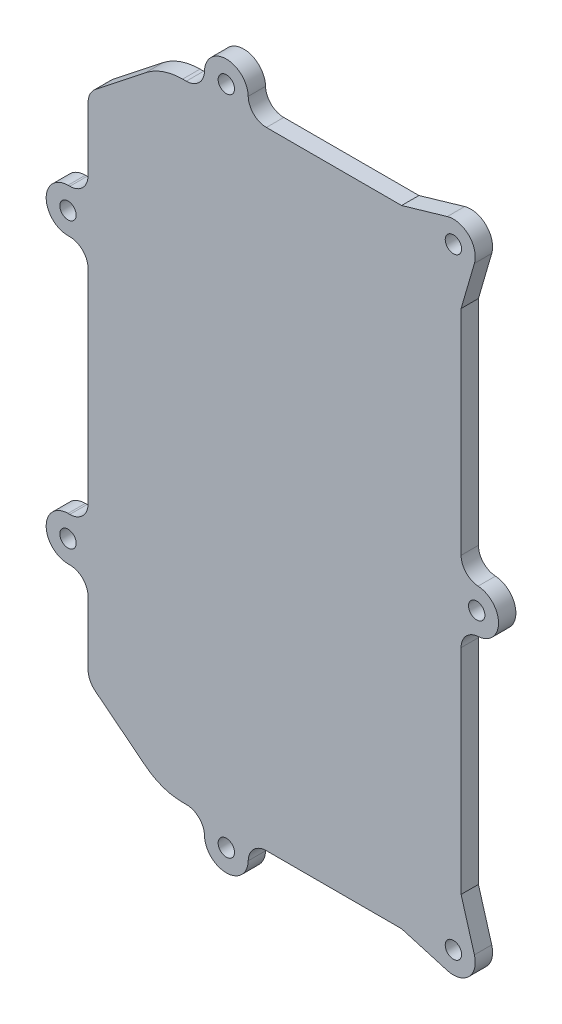
SolidWorks part; units mm, degrees
material "Acrylic (Medium-high impact)"
ref_plane "X-Y Datum" through (0, 0, 0) normal (0, 0, 1) x (1, 0, 0)
ref_plane "X-Z Datum" through (0, 0, 0) normal (0, 1, 0) x (1, 0, 0)
ref_plane "Y-Z Datum" through (0, 0, 0) normal (1, 0, 0) x (0, 0, -1)
sketch "Sketch1" plane through (0, 0, 0) normal (0, 0, 1) x (1, 0, 0)
  line L19 (-94.0226, 36.54) -> (-94.0226, 19.1784)
  line L20 (-99.5226, 41.54) -> (-99.0226, 41.54)
  line L21 (-99.0226, 53.54) -> (-99.5226, 53.54)
  line L22 (-94.0226, 114.5767) -> (-94.0226, 58.54)
  line L23 (-99.5226, 119.5767) -> (-99.0226, 119.5767)
  line L24 (-99.0226, 131.5767) -> (-99.5226, 131.5767)
  line L25 (-94.0226, 153.9383) -> (-94.0226, 136.5767)
  line L26 (-78.1621, 169.0446) -> (-91.9938, 158.1249)
  line L27 (-67.0387, 172.5583) -> (-68.0408, 172.5583)
  line L28 (-7.9166, 172.5583) -> (-45.043, 172.5583)
  line L31 (4.6315, 176.21) -> (-7.9166, 172.5583)
  line L33 (8.4174, 156.2243) -> (12.0691, 168.7725)
  line L35 (8.4174, 97.5349) -> (8.4174, 156.2243)
  line L36 (8.4174, 16.8923) -> (8.4174, 75.5817)
  line L38 (12.0691, 4.3442) -> (8.4174, 16.8923)
  line L39 (-7.9166, 0.5583) -> (4.6315, -3.0933)
  line L40 (-45.043, 0.5583) -> (-7.9166, 0.5583)
  line L42 (-68.0408, 0.5583) -> (-67.0387, 0.5583)
  line L43 (-91.9938, 14.9918) -> (-78.1621, 4.0721)
  line L94 (-94.0226, 36.54) -> (-94.0226, 19.1784)
  line L95 (-99.5226, 41.54) -> (-99.0226, 41.54)
  line L96 (-99.0226, 53.54) -> (-99.5226, 53.54)
  line L97 (-94.0226, 114.5767) -> (-94.0226, 58.54)
  line L98 (-99.5226, 119.5767) -> (-99.0226, 119.5767)
  line L99 (-99.0226, 131.5767) -> (-99.5226, 131.5767)
  line L100 (-94.0226, 153.9383) -> (-94.0226, 136.5767)
  line L101 (-78.1621, 169.0446) -> (-91.9938, 158.1249)
  line L102 (-67.0387, 172.5583) -> (-68.0408, 172.5583)
  line L103 (-7.9166, 172.5583) -> (-45.043, 172.5583)
  line L104 (4.6315, 176.21) -> (-7.9166, 172.5583)
  line L105 (8.4174, 156.2243) -> (12.0691, 168.7725)
  line L106 (8.4174, 97.5349) -> (8.4174, 156.2243)
  line L107 (8.4174, 16.8923) -> (8.4174, 75.5817)
  line L108 (12.0691, 4.3442) -> (8.4174, 16.8923)
  line L109 (-7.9166, 0.5583) -> (4.6315, -3.0933)
  line L110 (-45.043, 0.5583) -> (-7.9166, 0.5583)
  line L111 (-68.0408, 0.5583) -> (-67.0387, 0.5583)
  line L112 (-91.9938, 14.9918) -> (-78.1621, 4.0721)
  arc A21 (-94.0226, 36.54) -> (-99.0226, 41.54) centre (-99.0226, 36.54) ccw
  arc A22 (-99.5226, 53.54) -> (-99.5226, 41.54) centre (-99.5226, 47.54) ccw
  arc A23 (-99.0226, 53.54) -> (-94.0226, 58.54) centre (-99.0226, 58.54) ccw
  arc A24 (-94.0226, 114.5767) -> (-99.0226, 119.5767) centre (-99.0226, 114.5767) ccw
  arc A25 (-99.5226, 131.5767) -> (-99.5226, 119.5767) centre (-99.5226, 125.5767) ccw
  arc A26 (-99.0226, 131.5767) -> (-94.0226, 136.5767) centre (-99.0226, 136.5767) ccw
  arc A27 (-91.9938, 158.1249) -> (-94.0226, 153.9383) centre (-88.6886, 153.9383) ccw
  arc A63 (-68.0408, 172.5583) -> (-78.1621, 169.0446) centre (-68.0408, 156.2243) ccw
  arc A64 (-67.0387, 172.5583) -> (-62.0397, 177.4596) centre (-67.0387, 177.5583) ccw
  arc A65 (-50.042, 177.4596) -> (-62.0397, 177.4596) centre (-56.0408, 177.341) ccw
  arc A66 (-50.042, 177.4596) -> (-45.043, 172.5583) centre (-45.043, 177.5583) ccw
  arc A67 (12.0691, 168.7725) -> (4.6315, 176.21) centre (6.3081, 170.449) ccw
  arc A68 (8.4174, 97.5349) -> (13.0914, 92.5456) centre (13.4174, 97.5349) ccw
  arc A69 (13.0914, 80.5711) -> (13.0914, 92.5456) centre (12.7001, 86.5583) ccw
  arc A70 (13.0914, 80.5711) -> (8.4174, 75.5817) centre (13.4174, 75.5817) ccw
  arc A72 (4.6315, -3.0933) -> (12.0691, 4.3442) centre (6.3081, 2.6677) ccw
  arc A74 (-45.043, 0.5583) -> (-50.042, -4.3429) centre (-45.043, -4.4417) ccw
  arc A76 (-62.0397, -4.3429) -> (-50.042, -4.3429) centre (-56.0408, -4.2244) ccw
  arc A79 (-62.0397, -4.3429) -> (-67.0387, 0.5583) centre (-67.0387, -4.4417) ccw
  arc A83 (-78.1621, 4.0721) -> (-68.0408, 0.5583) centre (-68.0408, 16.8923) ccw
  arc A87 (-94.0226, 19.1784) -> (-91.9938, 14.9918) centre (-88.6886, 19.1784) ccw
  arc A91 (-94.0226, 36.54) -> (-99.0226, 41.54) centre (-99.0226, 36.54) ccw
  arc A95 (-99.5226, 53.54) -> (-99.5226, 41.54) centre (-99.5226, 47.54) ccw
  arc A99 (-99.0226, 53.54) -> (-94.0226, 58.54) centre (-99.0226, 58.54) ccw
  arc A122 (-94.0226, 114.5767) -> (-99.0226, 119.5767) centre (-99.0226, 114.5767) ccw
  arc A123 (-99.5226, 131.5767) -> (-99.5226, 119.5767) centre (-99.5226, 125.5767) ccw
  arc A124 (-99.0226, 131.5767) -> (-94.0226, 136.5767) centre (-99.0226, 136.5767) ccw
  arc A125 (-91.9938, 158.1249) -> (-94.0226, 153.9383) centre (-88.6886, 153.9383) ccw
  arc A126 (-68.0408, 172.5583) -> (-78.1621, 169.0446) centre (-68.0408, 156.2243) ccw
  arc A127 (-67.0387, 172.5583) -> (-62.0397, 177.4596) centre (-67.0387, 177.5583) ccw
  arc A128 (-50.042, 177.4596) -> (-62.0397, 177.4596) centre (-56.0408, 177.341) ccw
  arc A129 (-50.042, 177.4596) -> (-45.043, 172.5583) centre (-45.043, 177.5583) ccw
  arc A130 (12.0691, 168.7725) -> (4.6315, 176.21) centre (6.3081, 170.449) ccw
  arc A131 (8.4174, 97.5349) -> (13.0914, 92.5456) centre (13.4174, 97.5349) ccw
  arc A132 (13.0914, 80.5711) -> (13.0914, 92.5456) centre (12.7001, 86.5583) ccw
  arc A133 (13.0914, 80.5711) -> (8.4174, 75.5817) centre (13.4174, 75.5817) ccw
  arc A134 (4.6315, -3.0933) -> (12.0691, 4.3442) centre (6.3081, 2.6677) ccw
  arc A135 (-45.043, 0.5583) -> (-50.042, -4.3429) centre (-45.043, -4.4417) ccw
  arc A136 (-62.0397, -4.3429) -> (-50.042, -4.3429) centre (-56.0408, -4.2244) ccw
  arc A137 (-62.0397, -4.3429) -> (-67.0387, 0.5583) centre (-67.0387, -4.4417) ccw
  arc A138 (-78.1621, 4.0721) -> (-68.0408, 0.5583) centre (-68.0408, 16.8923) ccw
  arc A139 (-94.0226, 19.1784) -> (-91.9938, 14.9918) centre (-88.6886, 19.1784) ccw
  dimension "D1" = 0
extrude "Boss-Extrude1" add sketch "Sketch1" against normal blind 4.7625
hole_wizard "M4 Clearance Hole1" positions "Sketch4" profile "Sketch3" hole size "M4" standard "ANSI Metric" end condition through all
sketch "Sketch4" plane through (0, 0, -4.7625) normal (0, 0, -1) x (-1, 0, 0)
  point P6 (-12.7001, 86.5583)
  point P15 (-6.3081, 2.6677)
  point P20 (-6.3081, 170.449)
  point P21 (99.5226, 47.54)
  point P24 (99.5226, 125.5767)
  point P32 (56.0408, 177.341)
  point P35 (56.0408, -4.2244)
sketch "Sketch3" plane through (12.7001, 86.5583, -4.7625) normal (1, 0, 0) x (0, 1, 0)
  line L0 (0, 0) -> (0, 4.7625)
  line L1 (0, 4.7625) -> (2.25, 4.7625)
  line L2 (2.25, 4.7625) -> (2.25, 0)
  line L5 (2.25, 0) -> (0, 0)
  line L11 (0, -6.35) -> (0, 107.95) construction
  dimension "Thru Hole Dia." = 4.5
  dimension "Thru Hole Depth" = 4.7625
